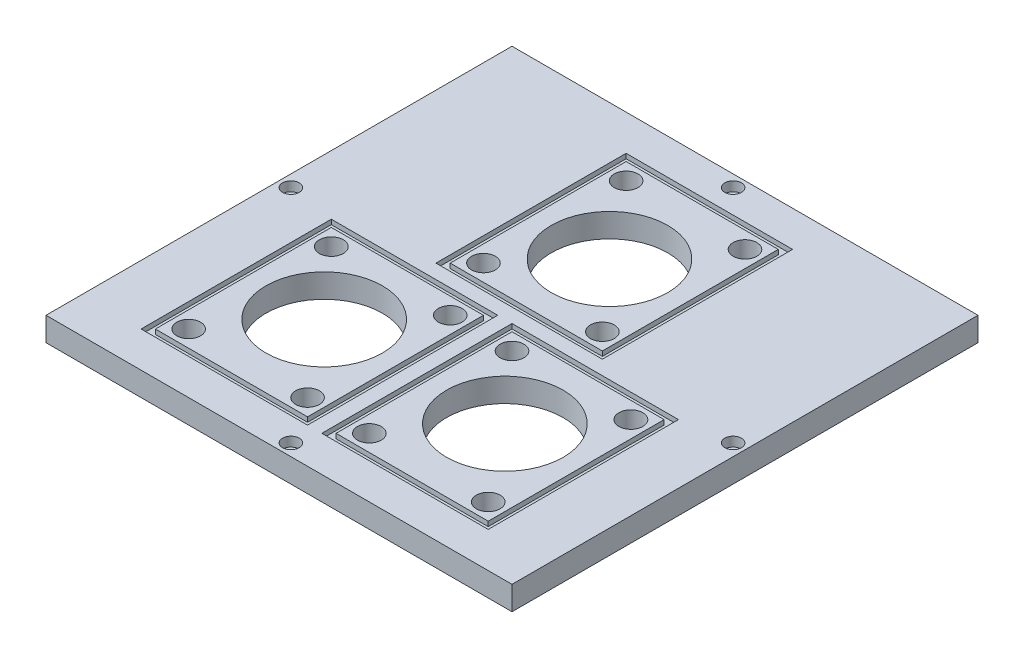
SolidWorks part; units mm, degrees
ref_plane "Front Plane" through (0, 0, 0) normal (0, 0, 1) x (1, 0, 0)
ref_plane "Top Plane" through (0, 0, 0) normal (0, 1, 0) x (1, 0, 0)
ref_plane "Right Plane" through (0, 0, 0) normal (1, 0, 0) x (0, 0, -1)
sketch "Sketch1" plane through (0, 0, 0) normal (0, 1, 0) x (1, 0, 0)
  line L1 (-49, 49) -> (49, 49)
  line L2 (-49, 49) -> (-49, -49)
  line L3 (-49, -49) -> (49, -49)
  line L4 (49, 49) -> (49, -49)
  line L5 (-49, 49) -> (49, -49) construction
  line L6 (-49, -49) -> (49, 49) construction
  point P0 (0, 0)
  dimension "D1" = 98
  dimension "D2" = 98
extrude "Boss-Extrude2" add sketch "Sketch1" along normal blind 5
sketch "Sketch3" plane through (0, 0, 0) normal (0, -1, 0) x (1, 0, 0)
  line L0 (0, 0) -> (0, 3) construction
  line L1 (0, 0) -> (0, -3) construction
  line L2 (0, 0) -> (3, 0) construction
  line L3 (0, 0) -> (-3, 0) construction
  line L4 (0, -3) -> (-3, -3) construction
  line L5 (-3, -3) -> (-3, 3) construction
  line L6 (-3, 3) -> (3, 3) construction
  line L7 (3, 3) -> (3, -3) construction
  line L8 (3, -3) -> (0, -3) construction
  line L9 (3, 0) -> (3, 3)
  line L10 (-16, -3) -> (16, -3) construction
  line L11 (16, -3) -> (16, -40) construction
  line L12 (-16, -3) -> (-16, -40) construction
  line L13 (-16, -40) -> (16, -40) construction
  line L14 (3, 3) -> (3, 40) construction
  line L15 (3, 40) -> (35, 40) construction
  line L16 (35, 40) -> (35, 3) construction
  line L17 (35, 3) -> (3, 3) construction
  line L18 (-35, 3) -> (-3, 3) construction
  line L19 (-35, 40) -> (-35, 3) construction
  line L20 (-3, 40) -> (-35, 40) construction
  line L21 (-3, 3) -> (-3, 40) construction
  line L22 (-30, 6.5) -> (-8, 6.5) construction
  line L24 (-30.8177, 35.1642) -> (-7.1823, 7.8358)
  line L25 (-31.5, 35) -> (-31.5, 8) construction
  line L26 (-30, 36.5) -> (-8, 36.5) construction
  line L27 (-6.5, 35) -> (-6.5, 8) construction
  line L28 (-35, 40) -> (-32.7235, 37.3678)
  line L29 (-35, 3) -> (-32.7235, 5.6322)
  line L30 (-5.2765, 37.3678) -> (-3, 40)
  line L31 (-30.8177, 7.8358) -> (-7.1823, 35.1642)
  line L32 (49, -49) -> (-49, -49) construction
  line L33 (-5.2765, 5.6322) -> (-3, 3)
  line L34 (-49, 49) -> (49, 49) construction
  circle A0 centre (-31.5, 36.5) radius 1.5
  circle A1 centre (-6.5, 36.5) radius 1.5
  circle A2 centre (-6.5, 6.5) radius 1.5
  circle A3 centre (-31.5, 6.5) radius 1.5
  circle A4 centre (31.5, 6.5) radius 1.5
  circle A5 centre (6.5, 6.5) radius 1.5
  circle A6 centre (6.5, 36.5) radius 1.5
  circle A7 centre (31.5, 36.5) radius 1.5
  circle A8 centre (12.5, -6.5) radius 1.5
  circle A9 centre (12.5, -36.5) radius 1.5
  circle A10 centre (-12.5, -6.5) radius 1.5
  circle A11 centre (-12.5, -36.5) radius 1.5
sketch "Sketch6" plane through (0, 5, 0) normal (0, 1, 0) x (1, 0, 0)
  circle A0 centre (-12.5, 36.5) radius 2.5
  circle A1 centre (12.5, 36.5) radius 2.5
  circle A2 centre (-12.5, 6.5) radius 2.5
  circle A3 centre (12.5, 6.5) radius 2.5
  circle A4 centre (-31.5, -6.5) radius 2.517
  circle A5 centre (-6.5, -6.5) radius 2.5
  circle A6 centre (-31.5, -36.5) radius 2.5
  circle A7 centre (-6.5, -36.5) radius 2.5
  circle A8 centre (6.5, -36.5) radius 2.5
  circle A9 centre (31.5, -36.5) radius 2.5
  circle A10 centre (6.5, -6.5) radius 2.5
  circle A11 centre (31.5, -6.5) radius 2.517
extrude "Cut-Extrude11" cut sketch "Sketch6" against normal blind 19
sketch "Sketch9" plane through (0, 0, 0) normal (0, -1, 0) x (1, 0, 0)
  line L0 (0, -40) -> (0, -20.5)
  line L1 (-16, -40) -> (16, -40) construction
  line L2 (19, 40) -> (19, 20.5)
  line L3 (3, 40) -> (35, 40) construction
  line L4 (0, 3) -> (0, 8.0141)
  line L5 (-3, 3) -> (3, 3) construction
  circle A0 centre (0, -20.5) radius 12.25
  circle A1 centre (19, 20.5) radius 12.25
  circle A2 centre (-19, 20.5) radius 12.25
extrude "Cut-Extrude10" cut sketch "Sketch9" against normal blind 19
sketch "Sketch10" plane through (0, 5, 0) normal (0, 1, 0) x (1, 0, 0)
  line L0 (-30.8177, -35.1642) -> (-7.1823, -7.8358) construction
  line L1 (-16, 40) -> (16, 40)
  line L2 (-16, 40) -> (-16, 3)
  line L3 (-16, 3) -> (16, 3)
  line L4 (16, 40) -> (16, 3)
  line L5 (0, -3) -> (0, -6.9737)
  line L6 (1.5, -1.5) -> (36.5, -1.5)
  line L7 (-35, -3) -> (-3, -3)
  line L8 (-35, -3) -> (-35, -40)
  line L9 (-35, -40) -> (-3, -40)
  line L10 (-3, -3) -> (-3, -40)
  line L11 (36.5, -41.5) -> (36.5, -1.5)
  line L12 (1.5, -41.5) -> (36.5, -41.5)
  line L13 (1.5, -41.5) -> (1.5, -1.5)
  line L14 (35, -40) -> (3, -40)
  line L15 (3, -3) -> (3, -40)
  line L16 (17.5, 1.5) -> (-17.5, 1.5)
  line L17 (17.5, 1.5) -> (17.5, 41.5)
  line L18 (17.5, 41.5) -> (-17.5, 41.5)
  line L19 (-17.5, 1.5) -> (-17.5, 41.5)
  line L20 (35, -3) -> (3, -3)
  line L21 (35, -3) -> (35, -40)
  line L24 (-1.5, -41.5) -> (-36.5, -41.5)
  line L25 (-1.5, -41.5) -> (-1.5, -1.5)
  line L26 (-1.5, -1.5) -> (-36.5, -1.5)
  line L27 (-36.5, -41.5) -> (-36.5, -1.5)
  point P0 (0, 21.5)
  point P6 (-19, -21.5)
  point P23 (0, 21.5)
  point P28 (-19, -21.5)
extrude "Cut-Extrude12" cut sketch "Sketch10" against normal blind 1 contours L19 L16 L17 L18 L1 L4 L3 L2 | L27 L24 L25 L26 L7 L10 L9 L8 | L13 L12 L11 L6 L20 L21 L14 L15
sketch "Sketch7" plane through (0, 5, 0) normal (0, 1, 0) x (1, 0, 0)
  line L1 (-16, 37) -> (16, 37)
  line L2 (-16, 37) -> (-16, 3)
  line L3 (-16, 3) -> (16, 3)
  line L4 (16, 37) -> (16, 3)
  line L8 (-30.8177, -35.1642) -> (-7.1823, -7.8358) construction
  line L9 (17.5, -1.5) -> (-17.5, -1.5)
  line L10 (17.5, -1.5) -> (17.5, 38.5)
  line L11 (17.5, 38.5) -> (-17.5, 38.5)
  line L12 (-17.5, -1.5) -> (-17.5, 38.5)
  line L15 (-35, -3) -> (-3, -3)
  line L16 (-35, -3) -> (-35, -40)
  line L17 (-35, -40) -> (-3, -40)
  line L18 (-3, -3) -> (-3, -40)
  line L19 (0, -1.5) -> (0, -10.4217)
  line L20 (1.5, -1.5) -> (36.5, -1.5)
  line L24 (-1.5, -41.5) -> (-36.5, -41.5)
  line L25 (-1.5, -41.5) -> (-1.5, -1.5)
  line L26 (-1.5, -1.5) -> (-36.5, -1.5)
  line L27 (-36.5, -41.5) -> (-36.5, -1.5)
  line L31 (36.5, -41.5) -> (36.5, -1.5)
  line L32 (1.5, -41.5) -> (36.5, -41.5)
  line L33 (1.5, -41.5) -> (1.5, -1.5)
  line L34 (35, -40) -> (3, -40)
  line L35 (3, -3) -> (3, -40)
  line L36 (35, -3) -> (3, -3)
  line L37 (35, -3) -> (35, -40)
  point P0 (0, 18.5)
  point P11 (0, 18.5)
  point P16 (-19, -21.5)
  point P28 (-19, -21.5)
sketch "Sketch11" plane through (0, 5, 0) normal (0, 1, 0) x (1, 0, 0)
  line L0 (49, -49) -> (49, 49) construction
  line L1 (-49, 49) -> (49, 49)
  line L2 (-49, 49) -> (-49, -49)
  line L3 (-49, -49) -> (49, -49)
  line L4 (49, 49) -> (49, -49)
  line L5 (-49, -49) -> (49, -49) construction
  line L7 (-46.5, 46.5) -> (46.5, 46.5)
  line L8 (-46.5, 46.5) -> (-46.5, -46.5)
  line L9 (-46.5, -46.5) -> (46.5, -46.5)
  line L10 (46.5, 46.5) -> (46.5, -46.5)
  line L11 (-44, 44) -> (44, 44)
  line L12 (-44, 44) -> (-44, -44)
  line L13 (-44, -44) -> (44, -44)
  line L14 (44, 44) -> (44, -44)
  line L15 (-44, 44) -> (44, -44) construction
  line L16 (-44, -44) -> (44, 44) construction
  point P9 (0, 0)
  point P15 (0, 0)
  dimension "D1" = 93
  dimension "D2" = 93
  dimension "D3" = 88
  dimension "D4" = 88
sketch "Sketch12" plane through (0, 0, 0) normal (0, -1, 0) x (1, 0, 0)
  line L1 (49, -49) -> (-49, -49) construction
  line L2 (49, -49) -> (49, 49) construction
  line L3 (49, 49) -> (-49, 49) construction
  line L4 (-49, -49) -> (-49, 49) construction
  line L5 (-44, 44) -> (44, 44)
  line L6 (-44, 44) -> (-44, -44)
  line L7 (-44, -44) -> (44, -44)
  line L8 (44, 44) -> (44, -44)
  line L9 (-39, 39) -> (39, 39)
  line L10 (-39, 39) -> (-39, -39)
  line L11 (-39, -39) -> (39, -39)
  line L12 (39, 39) -> (39, -39)
  line L13 (-39, 39) -> (39, -39) construction
  line L14 (-39, -39) -> (39, 39) construction
  point P0 (0, 0)
  point P7 (0, 0)
  point P12 (0, 0)
  dimension "D1" = 78
  dimension "D2" = 78
extrude "Boss-Extrude4" add sketch "Sketch12" along normal blind 2 contours L6 L5 L8 L7 | L10 L9 L12 L11
sketch "Sketch13" plane through (0, 5, 0) normal (0, 1, 0) x (1, 0, 0)
  line L0 (49, 0) -> (44, 0)
  line L1 (49, -49) -> (49, 49) construction
  line L2 (0, -49) -> (0, -44)
  line L3 (-49, -49) -> (49, -49) construction
  line L5 (-44, 44) -> (44, 44) construction
  line L6 (-44, 44) -> (-44, -44) construction
  line L7 (-44, -44) -> (44, -44) construction
  line L8 (44, 44) -> (44, -44) construction
  circle A0 centre (46.5, 0) radius 1.75
  circle A1 centre (-46.5, 0) radius 1.75
  circle A2 centre (0, -46.5) radius 1.75
  circle A3 centre (0, 46.5) radius 1.75
  point P9 (0, 0)
  dimension "D1" = 3.5
  dimension "D2" = 3.5
extrude "Cut-Extrude13" cut sketch "Sketch13" against normal blind 2 contours L2 A2 | L2 A2 | A1 | A3 | L0 A0 | L0 A0
sketch "Sketch14" plane through (0, 5, 0) normal (0, 1, 0) x (1, 0, 0)
  circle A0 centre (0, -46.5) radius 1
  circle A1 centre (-46.5, 0) radius 1
  circle A2 centre (46.5, 0) radius 1
  circle A3 centre (0, 46.5) radius 1
extrude "Cut-Extrude14" cut sketch "Sketch14" against normal blind 9
